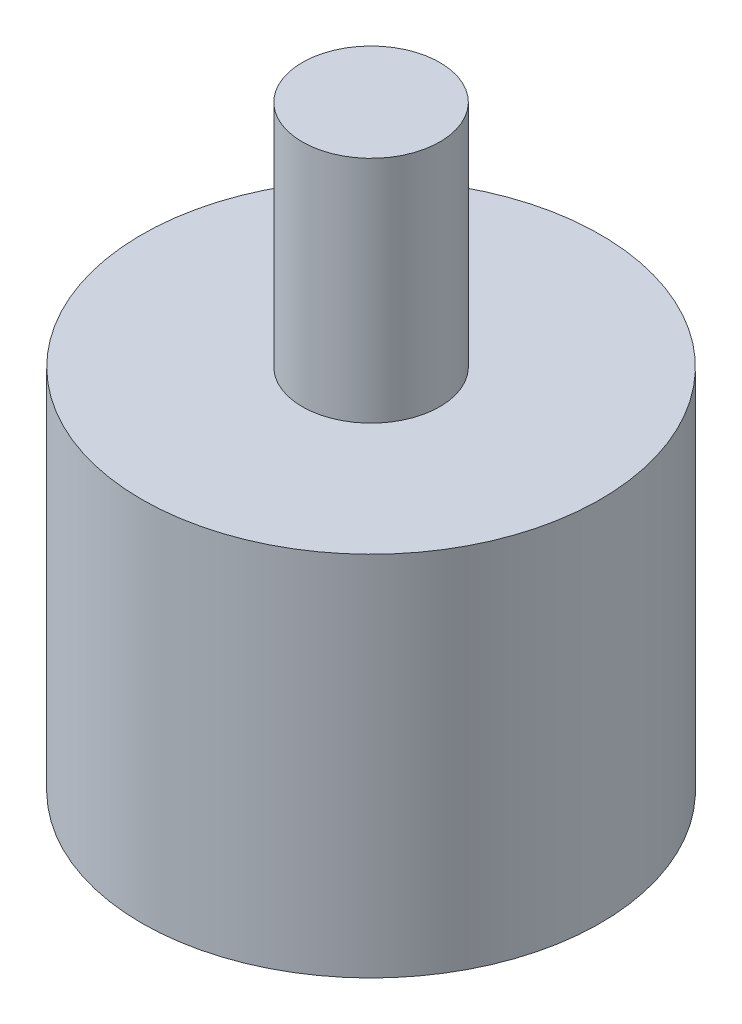
SolidWorks part; units mm, degrees
ref_plane "Front Plane" through (0, 0, 0) normal (0, 0, 1) x (1, 0, 0)
ref_plane "Top Plane" through (0, 0, 0) normal (0, 1, 0) x (1, 0, 0)
ref_plane "Right Plane" through (0, 0, 0) normal (1, 0, 0) x (0, 0, -1)
sketch "Sketch1" plane through (0, 0, 0) normal (0, 1, 0) x (1, 0, 0)
  circle A0 centre (0, 0) radius 5
  circle A1 centre (0, 0) radius 2.95
  dimension "D1" = 10
  dimension "D2" = 5.9
extrude "Boss-Extrude1" add sketch "Sketch1" along normal blind 5
sketch "Sketch2" plane through (0, 5, 0) normal (0, 1, 0) x (1, 0, 0)
  circle A0 centre (0, 0) radius 5
extrude "Boss-Extrude2" add sketch "Sketch2" along normal blind 3
sketch "Sketch3" plane through (0, 8, 0) normal (0, 1, 0) x (1, 0, 0)
  circle A0 centre (0, 0) radius 1.5
  dimension "D1" = 3
extrude "Boss-Extrude3" add sketch "Sketch3" along normal blind 5
